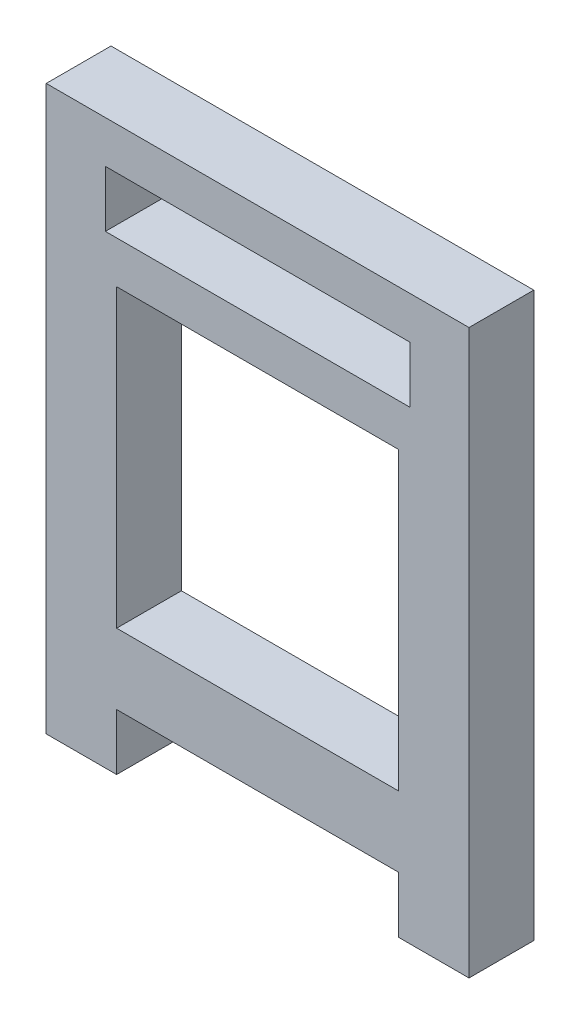
SolidWorks part; units mm, degrees
ref_plane "Front Plane" through (0, 0, 0) normal (0, 0, 1) x (1, 0, 0)
ref_plane "Top Plane" through (0, 0, 0) normal (0, 1, 0) x (1, 0, 0)
ref_plane "Right Plane" through (0, 0, 0) normal (1, 0, 0) x (0, 0, -1)
sketch "Sketch1" plane through (0, 0, 0) normal (0, 0, 1) x (1, 0, 0)
  line L0 (0, 0) -> (0, -2)
  line L1 (2.5, 0) -> (12.51, 0)
  line L2 (0, 0) -> (0, 18)
  line L3 (0, 18) -> (15.01, 18)
  line L4 (15.01, 0) -> (15.01, 18)
  line L5 (0, -2) -> (2.5, -2)
  line L6 (2.5, -2) -> (2.5, 0)
  line L7 (15.01, 0) -> (15.01, -2)
  line L8 (15.01, -2) -> (12.51, -2)
  line L9 (12.51, -2) -> (12.51, 0)
  line L12 (2.5, 2.5) -> (12.51, 2.5)
  line L13 (2.5, 2.5) -> (2.5, 13)
  line L14 (2.5, 13) -> (12.51, 13)
  line L15 (12.51, 2.5) -> (12.51, 13)
  line L16 (2.1, 14.5) -> (12.91, 14.5)
  line L17 (2.1, 14.5) -> (2.1, 16.5)
  line L18 (2.1, 16.5) -> (12.91, 16.5)
  line L19 (12.91, 14.5) -> (12.91, 16.5)
  dimension "D1" = 18
  dimension "D2" = 2.5
  dimension "D3" = 10.01
  dimension "D4" = 2
  dimension "D5" = 2
  dimension "D6" = 2.5
  dimension "D7" = 2.5
  dimension "D8" = 10.5
  dimension "D9" = 2
  dimension "D10" = 1.5
  dimension "D12" = 0.4
extrude "Boss-Extrude1" add sketch "Sketch1" along normal blind 2.3
